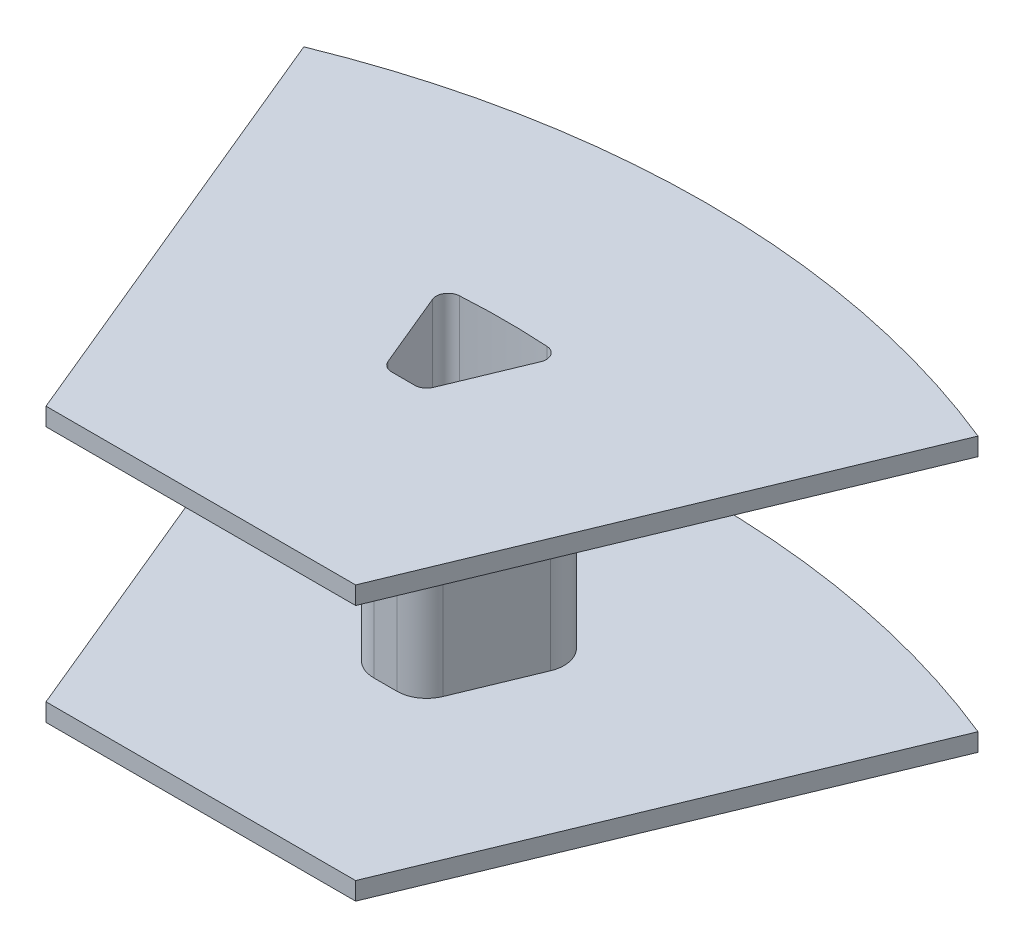
SolidWorks part; units mm, degrees
ref_plane "Front Plane" through (0, 0, 0) normal (0, 0, 1) x (1, 0, 0)
ref_plane "Top Plane" through (0, 0, 0) normal (0, 1, 0) x (1, 0, 0)
ref_plane "Right Plane" through (0, 0, 0) normal (1, 0, 0) x (0, 0, -1)
sketch "Sketch1" plane through (0, 0, 0) normal (0, 1, 0) x (1, 0, 0)
  line L0 (0, 0) -> (0, 105.1132) construction
  line L1 (-28.3079, 69.4526) -> (-13, 32.4962)
  line L2 (28.3079, 69.4526) -> (13, 32.4962)
  line L3 (-13, 32.4962) -> (13, 32.4962)
  line L4 (-4.543, 56.5023) -> (-1.8967, 50.1135)
  line L5 (-0.9728, 49.4962) -> (0.9728, 49.4962)
  line L6 (4.543, 56.5023) -> (1.8967, 50.1135)
  line L7 (-5.0714, 57.7779) -> (-1.641, 49.4962) construction
  line L8 (5.0714, 57.7779) -> (1.641, 49.4962) construction
  line L9 (-1.641, 49.4962) -> (1.641, 49.4962) construction
  arc A0 (28.3079, 69.4526) -> (-28.3079, 69.4526) centre (0, 0) ccw
  arc A1 (-13, 32.4962) -> (13, 32.4962) centre (0, 0) ccw construction
  arc A2 (0, 35) -> (-13, 32.4962) centre (0, 0) ccw construction
  arc A3 (13, 32.4962) -> (0, 35) centre (0, 0) ccw construction
  arc A4 (-28.3079, 69.4526) -> (28.3079, 69.4526) centre (0, 0) ccw construction
  arc A5 (3.6826, 57.883) -> (-3.6826, 57.883) centre (0, 0) ccw
  arc A6 (5.0714, 57.7779) -> (-5.0714, 57.7779) centre (0, 0) ccw construction
  arc A7 (-4.543, 56.5023) -> (-3.6826, 57.883) centre (-3.6191, 56.885) cw
  arc A8 (3.6826, 57.883) -> (4.543, 56.5023) centre (3.6191, 56.885) cw
  arc A9 (-1.8967, 50.1135) -> (-0.9728, 49.4962) centre (-0.9728, 50.4962) ccw
  arc A10 (1.8967, 50.1135) -> (0.9728, 49.4962) centre (0.9728, 50.4962) cw
  dimension "D1" = 150
  dimension "D2" = 70
  dimension "D6" = 1
  dimension "D7" = 1
  dimension "D3" = 22.5
  dimension "D4" = 26
  dimension "D5" = 17
extrude "Boss-Extrude1" add sketch "Sketch1" along normal mid plane 1.5
sketch "Sketch2" plane through (0, -0.75, 0) normal (0, -1, 0) x (1, 0, 0)
  line L0 (1.8967, -50.1135) -> (4.543, -56.5023) construction
  line L1 (-4.543, -56.5023) -> (-1.8967, -50.1135) construction
  line L2 (-0.9728, -49.4962) -> (0.9728, -49.4962) construction
  line L3 (1.8967, -50.1135) -> (4.543, -56.5023)
  line L4 (-4.543, -56.5023) -> (-1.8967, -50.1135)
  line L5 (-0.9728, -49.4962) -> (0.9728, -49.4962)
  line L6 (-0.9728, -47.9962) -> (0.9728, -47.9962)
  line L7 (-5.9288, -55.9283) -> (-3.2825, -49.5394)
  line L8 (3.2825, -49.5394) -> (5.9288, -55.9283)
  arc A0 (1.8967, -50.1135) -> (0.9728, -49.4962) centre (0.9728, -50.4962) ccw construction
  arc A1 (3.6826, -57.883) -> (4.543, -56.5023) centre (3.6191, -56.885) ccw construction
  arc A2 (-3.6826, -57.883) -> (3.6826, -57.883) centre (0, 0) ccw construction
  arc A3 (-4.543, -56.5023) -> (-3.6826, -57.883) centre (-3.6191, -56.885) ccw construction
  arc A4 (-0.9728, -49.4962) -> (-1.8967, -50.1135) centre (-0.9728, -50.4962) ccw construction
  arc A5 (1.8967, -50.1135) -> (0.9728, -49.4962) centre (0.9728, -50.4962) ccw
  arc A6 (3.6826, -57.883) -> (4.543, -56.5023) centre (3.6191, -56.885) ccw
  arc A7 (-3.6826, -57.883) -> (3.6826, -57.883) centre (0, 0) ccw
  arc A8 (-4.543, -56.5023) -> (-3.6826, -57.883) centre (-3.6191, -56.885) ccw
  arc A9 (-0.9728, -49.4962) -> (-1.8967, -50.1135) centre (-0.9728, -50.4962) ccw
  arc A10 (3.2825, -49.5394) -> (0.9728, -47.9962) centre (0.9728, -50.4962) ccw
  arc A11 (-0.9728, -47.9962) -> (-3.2825, -49.5394) centre (-0.9728, -50.4962) ccw
  arc A12 (-5.9288, -55.9283) -> (-3.7779, -59.3799) centre (-3.6191, -56.885) ccw
  arc A13 (-3.7779, -59.3799) -> (3.7779, -59.3799) centre (0, 0) ccw
  arc A14 (3.7779, -59.3799) -> (5.9288, -55.9283) centre (3.6191, -56.885) ccw
  dimension "D1" = 1.5
extrude "Boss-Extrude2" add sketch "Sketch2" along normal blind 20
ref_plane "Plane1" through (0, -10.75, 0) normal (0, -1, 0) x (-1, 0, 0)
mirror "Mirror1" about plane through (0, -10.75, 0) normal (0, -1, 0) of "Boss-Extrude1"
